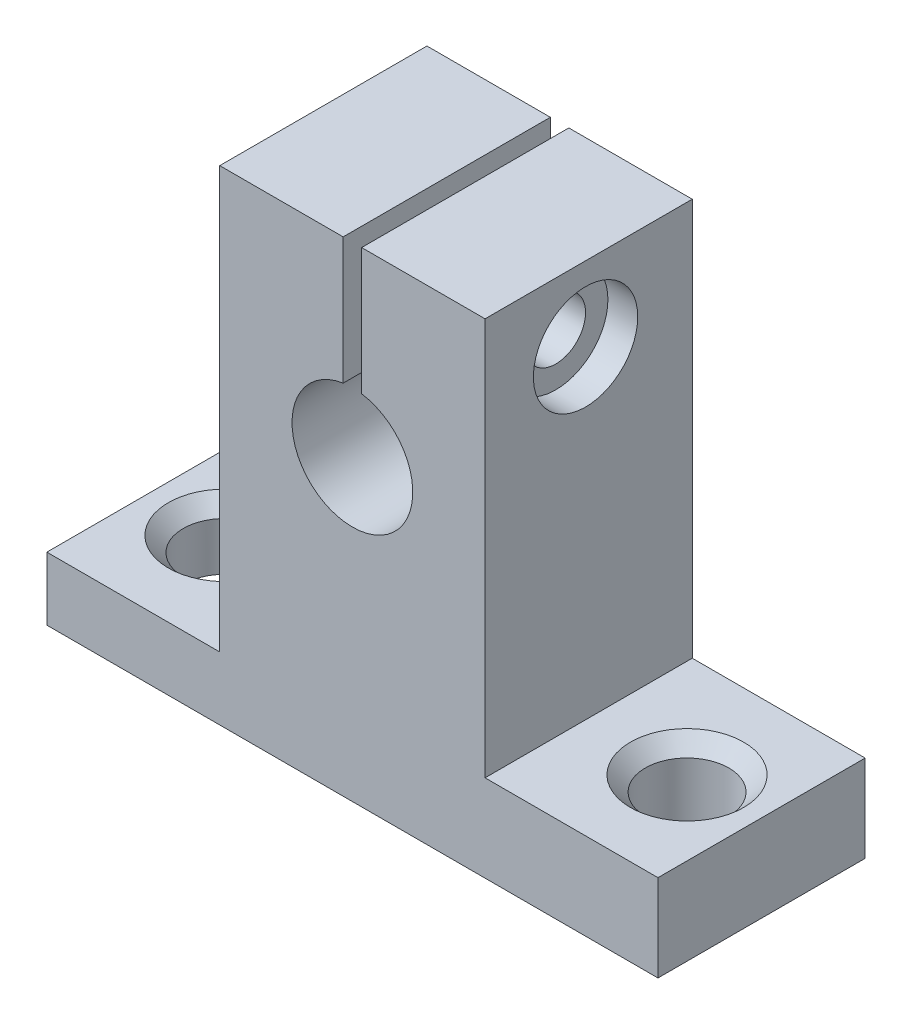
SolidWorks part; units mm, degrees
ref_plane "前基準面" through (0, 0, 0) normal (0, 0, 1) x (1, 0, 0)
ref_plane "上基準面" through (0, 0, 0) normal (0, 1, 0) x (1, 0, 0)
ref_plane "右基準面" through (0, 0, 0) normal (1, 0, 0) x (0, 0, -1)
sketch "草圖1" plane through (0, 0, 0) normal (0, 0, 1) x (1, 0, 0)
  line L0 (0, 0) -> (41000, 0)
  line L1 (41000, 0) -> (41000, 5830)
  line L2 (41000, 5830) -> (29400, 5830)
  line L3 (29400, 5830) -> (29400, 32500)
  line L4 (29400, 32500) -> (21120, 32500)
  line L5 (11600, 32500) -> (11600, 4243.4402)
  line L6 (11600, 4243.4402) -> (0, 4243.4402)
  line L7 (0, 4243.4402) -> (0, 0)
  line L8 (20500, 0) -> (20500, 27453.965) construction
  line L9 (19880, 24002.2619) -> (19880, 32500)
  line L10 (21120, 24002.2619) -> (21120, 32500)
  line L11 (19880, 32500) -> (11600, 32500)
  arc A0 (19880, 24002.2619) -> (21120, 24002.2619) centre (20500, 20000) ccw
  dimension "D5" = 8100
  dimension "D6" = 20000
  dimension "D1" = 41000
  dimension "D2" = 17800
  dimension "D3" = 5830
  dimension "D4" = 32500
  dimension "D7" = 1240
extrude "填料-伸長1" add sketch "草圖1" along normal blind 13900
sketch "草圖2" plane through (0, 5830, 0) normal (0, 1, 0) x (1, 0, 0)
  line L0 (41000, -13900) -> (41000, 0) construction
  line L1 (0, -13900) -> (0, 0) construction
  circle A0 centre (36000, -6950) radius 2800
  circle A1 centre (5000, -6950) radius 2800
  dimension "D1" = 5600
  dimension "D2" = 5600
  dimension "D3" = 5000
  dimension "D4" = 5000
extrude "除料-伸長1" cut sketch "草圖2" against normal blind 13900
chamfer "導角1" distance 1000 angle 45 2 edges at (33200, 5830, 6950) (7800, 4243.4402, 6950)
sketch "草圖3" plane through (29400, 0, 0) normal (1, 0, 0) x (0, 0, -1)
  line L0 (-13900, 32500) -> (0, 32500) construction
  circle A0 centre (-7158.2763, 27500) radius 3500
  dimension "D2" = 7000
  dimension "D1" = 5000
extrude "除料-伸長3" cut sketch "草圖3" against normal blind 2000 contours A0
sketch "草圖10" plane through (27400, 0, 0) normal (1, 0, 0) x (0, 0, -1)
  circle A0 centre (-7158.2763, 27500) radius 2000
  dimension "D1" = 4000
extrude "除料-伸長4" cut sketch "草圖10" against normal blind 24538
